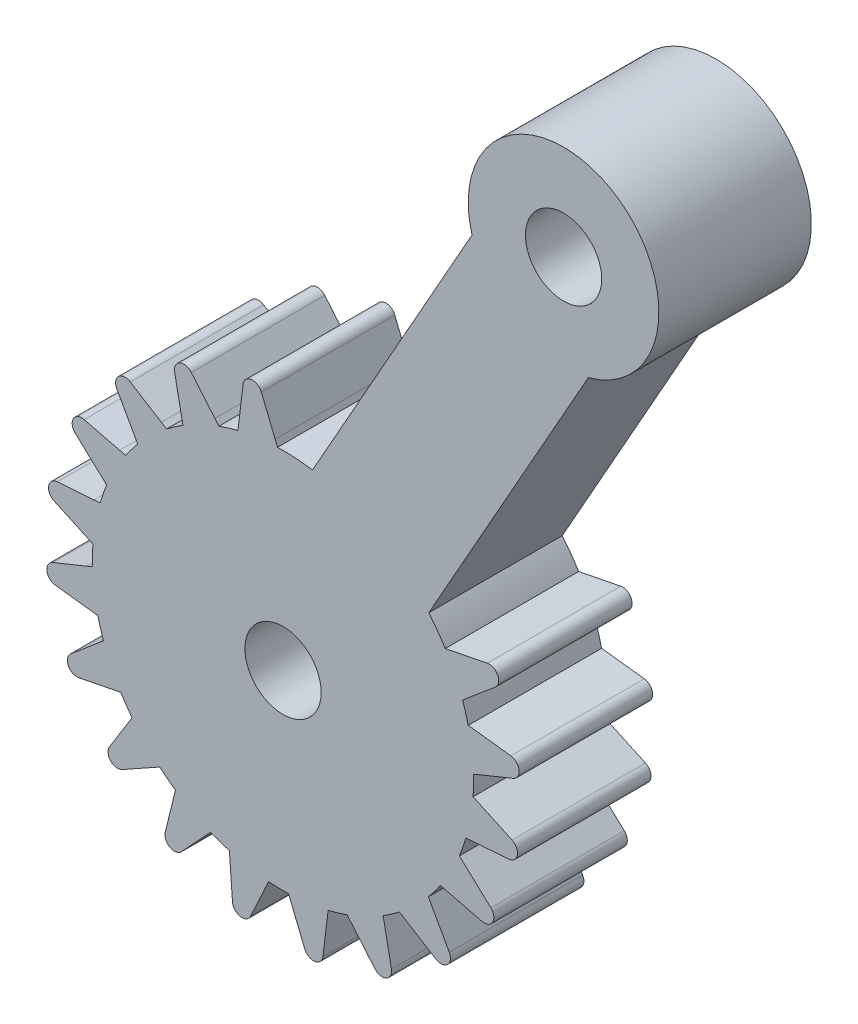
SolidWorks part; units mm, degrees
ref_plane "Front Plane" through (0, 0, 0) normal (0, 0, 1) x (1, 0, 0)
ref_plane "Top Plane" through (0, 0, 0) normal (0, 1, 0) x (1, 0, 0)
ref_plane "Right Plane" through (0, 0, 0) normal (1, 0, 0) x (0, 0, -1)
ref_plane "Plane1" through (0, 0, 74) normal (0, 0, -1) x (-1, 0, 0)
sketch "Sketch1" plane through (0, 0, 74) normal (0, 0, -1) x (-1, 0, 0)
  line L0 (-9.7929, 22.0237) -> (-18.164, 36.8907)
  line L1 (-24.2635, 33.4563) -> (-15.8924, 18.5892)
  line L2 (-16.7571, 17.3948) -> (-18.9657, 17.8316)
  line L3 (-19.3799, 16.9546) -> (-17.9109, 15.7157)
  line L4 (-17.9109, 15.7157) -> (-17.6649, 15.5048)
  line L5 (-17.9632, 14.5079) -> (-20.1986, 14.2408)
  line L6 (-20.3216, 13.2787) -> (-18.5416, 12.5544)
  line L7 (-18.5416, 12.5544) -> (-18.2425, 12.4299)
  line L8 (-18.2181, 11.3896) -> (-20.2616, 10.4448)
  line L9 (-20.0813, 9.4918) -> (-18.1646, 9.353)
  line L10 (-18.1646, 9.353) -> (-17.8416, 9.327)
  line L11 (-17.497, 8.3452) -> (-19.1485, 6.8151)
  line L12 (-18.6825, 5.9645) -> (-16.8167, 6.4248)
  line L13 (-16.8167, 6.4248) -> (-16.5015, 6.4998)
  line L14 (-15.8704, 5.6726) -> (-16.9682, 3.707)
  line L15 (-16.2622, 3.0421) -> (-14.6299, 4.0564)
  line L16 (-14.6299, 4.0564) -> (-14.3534, 4.2252)
  line L17 (-13.4975, 3.6334) -> (-13.9342, 1.4248)
  line L18 (-13.0572, 1.0106) -> (-11.8183, 2.4796)
  line L19 (-11.8183, 2.4796) -> (-11.6075, 2.7256)
  line L20 (-10.6106, 2.4274) -> (-10.3435, 0.1919)
  line L21 (-9.3814, 0.069) -> (-8.6571, 1.8489)
  line L22 (-8.6571, 1.8489) -> (-8.5326, 2.148)
  line L23 (-7.4923, 2.1724) -> (-6.5475, 0.1289)
  line L24 (-5.5945, 0.3093) -> (-5.4557, 2.226)
  line L25 (-5.4557, 2.226) -> (-5.4297, 2.5489)
  line L26 (-4.4479, 2.8936) -> (-2.9178, 1.242)
  line L27 (-2.0672, 1.7081) -> (-2.5274, 3.5738)
  line L28 (-2.5274, 3.5738) -> (-2.6025, 3.889)
  line L29 (-1.7753, 4.5202) -> (0.1903, 3.4223)
  line L30 (0.8552, 4.1284) -> (-0.159, 5.7606)
  line L31 (-0.159, 5.7606) -> (-0.3278, 6.0371)
  line L32 (0.2639, 6.8931) -> (2.4725, 6.4563)
  line L33 (2.8867, 7.3333) -> (1.4177, 8.5722)
  line L34 (1.4177, 8.5722) -> (1.1717, 8.7831)
  line L35 (1.47, 9.78) -> (3.7054, 10.0471)
  line L36 (3.8284, 11.0091) -> (2.0484, 11.7335)
  line L37 (2.0484, 11.7335) -> (1.7493, 11.858)
  line L38 (1.7249, 12.8982) -> (3.7684, 13.8431)
  line L39 (3.588, 14.796) -> (1.6714, 14.9349)
  line L40 (1.6714, 14.9349) -> (1.3484, 14.9609)
  line L41 (1.0038, 15.9427) -> (2.6553, 17.4728)
  line L42 (2.1893, 18.3234) -> (0.3235, 17.8631)
  line L43 (0.3235, 17.8631) -> (0.0083, 17.788)
  line L44 (-0.6228, 18.6153) -> (0.475, 20.5808)
  line L45 (-0.231, 21.2458) -> (-1.8633, 20.2315)
  line L46 (-1.8633, 20.2315) -> (-2.1398, 20.0627)
  line L47 (-2.9957, 20.6544) -> (-2.559, 22.863)
  line L48 (-3.436, 23.2772) -> (-4.6749, 21.8082)
  line L49 (-4.6749, 21.8082) -> (-4.8857, 21.5622)
  line L50 (-5.8826, 21.8605) -> (-6.1497, 24.096)
  line L51 (-7.1118, 24.2189) -> (-7.8361, 22.4389)
  line L52 (-7.8361, 22.4389) -> (-7.9606, 22.1398)
  arc A0 (-18.164, 36.8907) -> (-24.2635, 33.4563) centre (-22.9657, 38.2849) ccw
  arc A1 (-15.8924, 18.5892) -> (-16.7571, 17.3948) centre (-8.2466, 12.1439) ccw
  arc A2 (-18.9657, 17.8316) -> (-19.3799, 16.9546) centre (-19.0627, 17.3411) ccw
  arc A3 (-17.6649, 15.5048) -> (-17.9632, 14.5079) centre (-8.2466, 12.1439) ccw
  arc A4 (-20.1986, 14.2408) -> (-20.3216, 13.2787) centre (-20.1393, 13.7443) ccw
  arc A5 (-18.2425, 12.4299) -> (-18.2181, 11.3896) centre (-8.2466, 12.1439) ccw
  arc A6 (-20.2616, 10.4448) -> (-20.0813, 9.4918) centre (-20.0518, 9.991) ccw
  arc A7 (-17.8416, 9.327) -> (-17.497, 8.3452) centre (-8.2466, 12.1439) ccw
  arc A8 (-19.1485, 6.8151) -> (-18.6825, 5.9645) centre (-18.8087, 6.4483) ccw
  arc A9 (-16.5015, 6.4998) -> (-15.8704, 5.6726) centre (-8.2466, 12.1439) ccw
  arc A10 (-16.9682, 3.707) -> (-16.2622, 3.0421) centre (-16.5317, 3.4632) ccw
  arc A11 (-14.3534, 4.2252) -> (-13.4975, 3.6334) centre (-8.2466, 12.1439) ccw
  arc A12 (-13.9342, 1.4248) -> (-13.0572, 1.0106) centre (-13.4437, 1.3278) ccw
  arc A13 (-11.6075, 2.7256) -> (-10.6106, 2.4274) centre (-8.2466, 12.1439) ccw
  arc A14 (-10.3435, 0.1919) -> (-9.3814, 0.069) centre (-9.847, 0.2512) ccw
  arc A15 (-8.5326, 2.148) -> (-7.4923, 2.1724) centre (-8.2466, 12.1439) ccw
  arc A16 (-6.5475, 0.1289) -> (-5.5945, 0.3093) centre (-6.0936, 0.3387) ccw
  arc A17 (-5.4297, 2.5489) -> (-4.4479, 2.8936) centre (-8.2466, 12.1439) ccw
  arc A18 (-2.9178, 1.242) -> (-2.0672, 1.7081) centre (-2.551, 1.5818) ccw
  arc A19 (-2.6025, 3.889) -> (-1.7753, 4.5202) centre (-8.2466, 12.1439) ccw
  arc A20 (0.1903, 3.4223) -> (0.8552, 4.1284) centre (0.4341, 3.8588) ccw
  arc A21 (-0.3278, 6.0371) -> (0.2639, 6.8931) centre (-8.2466, 12.1439) ccw
  arc A22 (2.4725, 6.4563) -> (2.8867, 7.3333) centre (2.5695, 6.9468) ccw
  arc A23 (1.1717, 8.7831) -> (1.47, 9.78) centre (-8.2466, 12.1439) ccw
  arc A24 (3.7054, 10.0471) -> (3.8284, 11.0091) centre (3.6461, 10.5435) ccw
  arc A25 (1.7493, 11.858) -> (1.7249, 12.8982) centre (-8.2466, 12.1439) ccw
  arc A26 (3.7684, 13.8431) -> (3.588, 14.796) centre (3.5586, 14.2969) ccw
  arc A27 (1.3484, 14.9609) -> (1.0038, 15.9427) centre (-8.2466, 12.1439) ccw
  arc A28 (2.6553, 17.4728) -> (2.1893, 18.3234) centre (2.3155, 17.8395) ccw
  arc A29 (0.0083, 17.788) -> (-0.6228, 18.6153) centre (-8.2466, 12.1439) ccw
  arc A30 (0.475, 20.5808) -> (-0.231, 21.2458) centre (0.0385, 20.8247) ccw
  arc A31 (-2.1398, 20.0627) -> (-2.9957, 20.6544) centre (-8.2466, 12.1439) ccw
  arc A32 (-2.559, 22.863) -> (-3.436, 23.2772) centre (-3.0495, 22.96) ccw
  arc A33 (-4.8857, 21.5622) -> (-5.8826, 21.8605) centre (-8.2466, 12.1439) ccw
  arc A34 (-6.1497, 24.096) -> (-7.1118, 24.2189) centre (-6.6462, 24.0367) ccw
  arc A35 (-7.9606, 22.1398) -> (-9.7929, 22.0237) centre (-8.2466, 12.1439) ccw
extrude "Boss-Extrude1" add sketch "Sketch1" against normal blind 7
sketch "Sketch2" plane through (0, 0, 74) normal (0, 0, -1) x (-1, 0, 0)
  circle A0 centre (-22.9657, 38.2849) radius 5
extrude "Boss-Extrude2" add sketch "Sketch2" along normal blind 1
ref_plane "Plane2" through (0, 12.1439, 0) normal (0, 1, 0) x (1, 0, 0)
sketch "Sketch3" plane through (0, 12.1439, 0) normal (0, 1, 0) x (1, 0, 0)
  line L0 (13.2466, -73) -> (8.2466, -73)
  line L1 (8.2466, -73) -> (8.2466, -74)
  line L2 (8.2466, -74) -> (13.2466, -74)
  line L3 (13.2466, -74) -> (13.2466, -73)
  line L4 (8.2466, -73) -> (8.2466, -74) construction
revolve "Revolve1" add sketch "Sketch3" angle 360 about L4
hole_wizard "Ø4.0 (4) Diameter Hole1" positions "Sketch5" profile "Sketch4" hole size "Ø4.0" standard "ANSI Metric"
sketch "Sketch5" plane through (0, 0, 81) normal (0, 0, 1) x (1, 0, 0)
  point P0 (22.9657, 38.2849)
  point P1 (8.2466, 12.1439)
sketch "Sketch4" plane through (22.9657, 38.2849, 81) normal (1, 0, 0) x (0, -1, 0)
  line L0 (0, 0) -> (0, 8)
  line L1 (0, 8) -> (2, 8)
  line L2 (2, 8) -> (2, 0)
  line L5 (2, 0) -> (0, 0)
  line L11 (0, -6.35) -> (0, 107.95) construction
  dimension "Thru Hole Dia." = 4
  dimension "Thru Hole Depth" = 8
